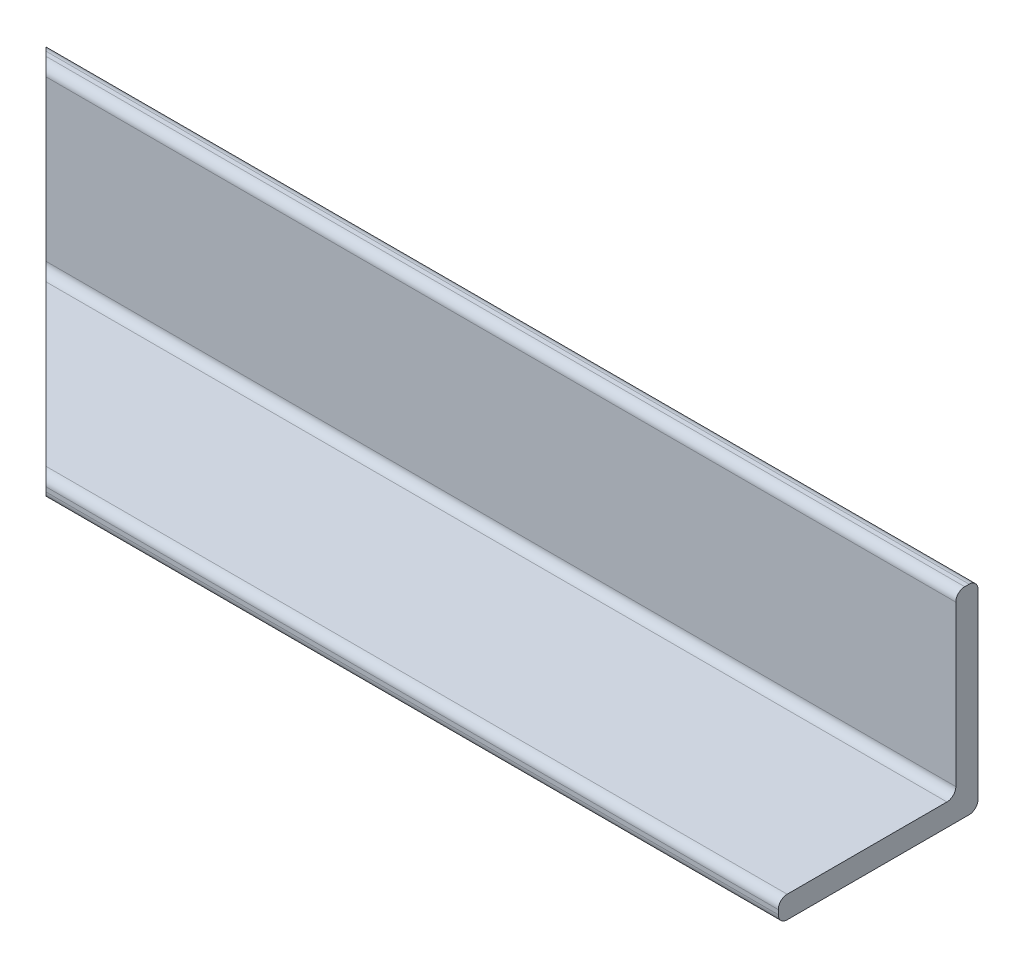
SolidWorks part; units mm, degrees
ref_plane "Front Plane" through (0, 0, 0) normal (0, 0, 1) x (1, 0, 0)
ref_plane "Top Plane" through (0, 0, 0) normal (0, 1, 0) x (1, 0, 0)
ref_plane "Right Plane" through (0, 0, 0) normal (1, 0, 0) x (0, 0, -1)
sketch "Sketch1" plane through (0, 0, 0) normal (0, 1, 0) x (1, 0, 0)
  line L1 (-52.5, 11.25) -> (52.5, 11.25)
  line L2 (-52.5, 11.25) -> (-52.5, -11.25)
  line L3 (-52.5, -11.25) -> (52.5, -11.25)
  line L4 (52.5, 11.25) -> (52.5, -11.25)
  line L5 (-52.5, 11.25) -> (52.5, -11.25) construction
  line L6 (-52.5, -11.25) -> (52.5, 11.25) construction
  point P0 (0, 0)
  dimension "D1" = 105
  dimension "D2" = 22.5
extrude "Boss-Extrude1" add sketch "Sketch1" along normal blind 2.5
sketch "Sketch2" plane through (0, 2.5, 0) normal (0, 1, 0) x (1, 0, 0)
  line L0 (52.5, -11.25) -> (52.5, 11.25) construction
  line L1 (-52.5, 11.25) -> (52.5, 11.25)
  line L2 (-52.5, 11.25) -> (-52.5, 8.75)
  line L3 (-52.5, 8.75) -> (52.5, 8.75)
  line L4 (52.5, 11.25) -> (52.5, 8.75)
  dimension "D1" = 2.5
extrude "Boss-Extrude2" add sketch "Sketch2" along normal blind 20
sketch "Sketch3" plane through (0, 0, 0) normal (0, -1, 0) x (-1, 0, 0)
  line L0 (52.5, -11.25) -> (52.5, 11.25)
  line L1 (52.5, 11.25) -> (30, -11.25)
  line L2 (52.5, -11.25) -> (-52.5, -11.25) construction
  line L3 (52.5, -11.25) -> (30, -11.25)
  line L4 (30, -11.25) -> (22.5808, -14.9716)
  dimension "D1" = 45
extrude "Cut-Extrude1" cut sketch "Sketch3" against normal through all contours L1 L0 L3
fillet "Fillet1" radius 1 6 edges at (0, 0, -11.25) (11.25, 0, 11.25) (11.25, 2.5, 11.25) (1.25, 2.5, -8.75) (0, 22.5, -11.25) (1.25, 22.5, -8.75)
